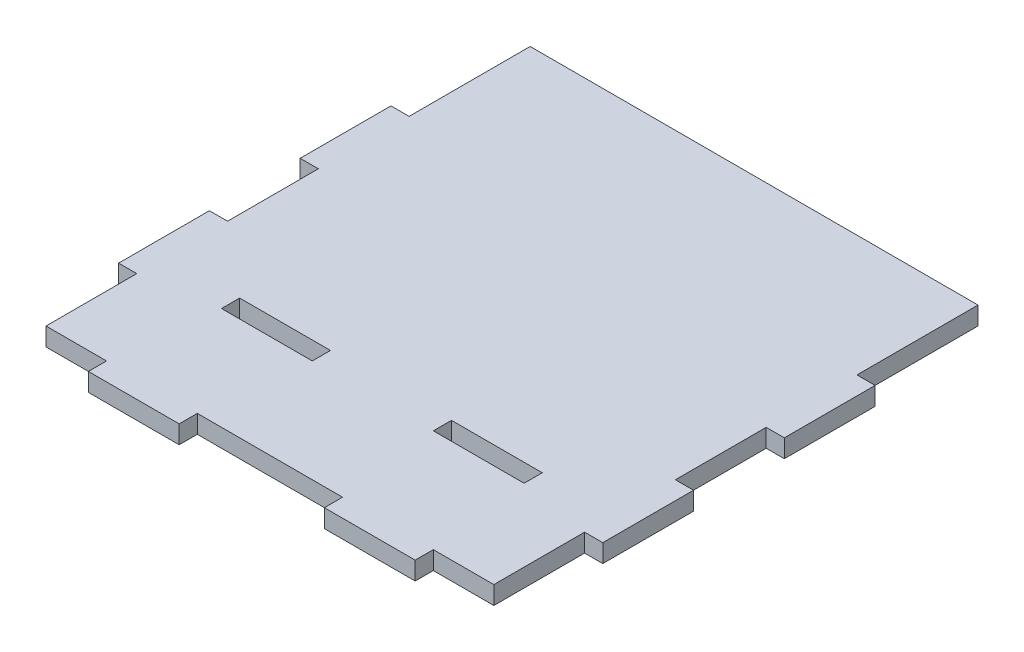
SolidWorks part; units mm, degrees
ref_plane "前视基准面" through (0, 0, 0) normal (0, 0, 1) x (1, 0, 0)
ref_plane "上视基准面" through (0, 0, 0) normal (0, 1, 0) x (1, 0, 0)
ref_plane "右视基准面" through (0, 0, 0) normal (1, 0, 0) x (0, 0, -1)
other "Configuration Table"
sketch "草图1" plane through (0, 0, 0) normal (0, 1, 0) x (1, 0, 0)
  line L0 (0, 19.0029) -> (0, -13.2551) construction
  line L1 (-37, 40) -> (37, 40)
  line L2 (-37, 40) -> (-37, -40)
  line L3 (-37, -40) -> (37, -40)
  line L4 (37, 40) -> (37, -40)
  line L5 (-37, 40) -> (37, -40) construction
  line L6 (-37, -40) -> (37, 40) construction
  line L7 (-37, 20) -> (-40, 20)
  line L8 (-37, 20) -> (-37, 5)
  line L9 (-37, 5) -> (-40, 5)
  line L10 (-40, 20) -> (-40, 5)
  line L11 (-37, -10) -> (-40, -10)
  line L12 (-37, -10) -> (-37, -25)
  line L13 (-37, -25) -> (-40, -25)
  line L14 (-40, -10) -> (-40, -25)
  line L15 (40, -10) -> (40, -25)
  line L16 (37, -25) -> (40, -25)
  line L17 (37, -10) -> (37, -25)
  line L18 (37, -10) -> (40, -10)
  line L19 (40, 20) -> (40, 5)
  line L20 (37, 5) -> (40, 5)
  line L21 (37, 20) -> (37, 5)
  line L22 (37, 20) -> (40, 20)
  line L23 (27, -43) -> (12, -43)
  line L24 (-27, -40) -> (-12, -40)
  line L25 (-27, -40) -> (-27, -43)
  line L26 (-27, -43) -> (-12, -43)
  line L27 (-12, -40) -> (-12, -43)
  line L28 (12, -40) -> (12, -43)
  line L29 (27, -40) -> (12, -40)
  line L30 (27, -40) -> (27, -43)
  point P0 (0, 0)
  dimension "D1" = 80
  dimension "D2" = 74
  dimension "D3" = 3
  dimension "D4" = 15
  dimension "D5" = 15
  dimension "D6" = 15
  dimension "D7" = 12
extrude "凸台-拉伸1" add sketch "草图1" along normal blind 3 contours L4 L1 L2 L3 | L11 L14 L13 L2 | L27 L3 L25 L26 | L30 L3 L28 L23 | L18 L4 L16 L15 | L22 L4 L20 L19 | L10 L9 L8 L7
sketch "草图2" plane through (0, 3, 0) normal (0, 1, 0) x (1, 0, 0)
  line L0 (0, 12.1782) -> (0, -7.2127) construction
  line L1 (-25, -20) -> (-10, -20)
  line L2 (-25, -20) -> (-25, -23)
  line L3 (-25, -23) -> (-10, -23)
  line L4 (-10, -20) -> (-10, -23)
  line L5 (25, -23) -> (10, -23)
  line L6 (10, -20) -> (10, -23)
  line L7 (25, -20) -> (10, -20)
  line L8 (25, -20) -> (25, -23)
  dimension "D1" = 3
  dimension "D2" = 15
  dimension "D3" = 10
  dimension "D4" = 23
extrude "切除-拉伸1" cut sketch "草图2" against normal blind 3
